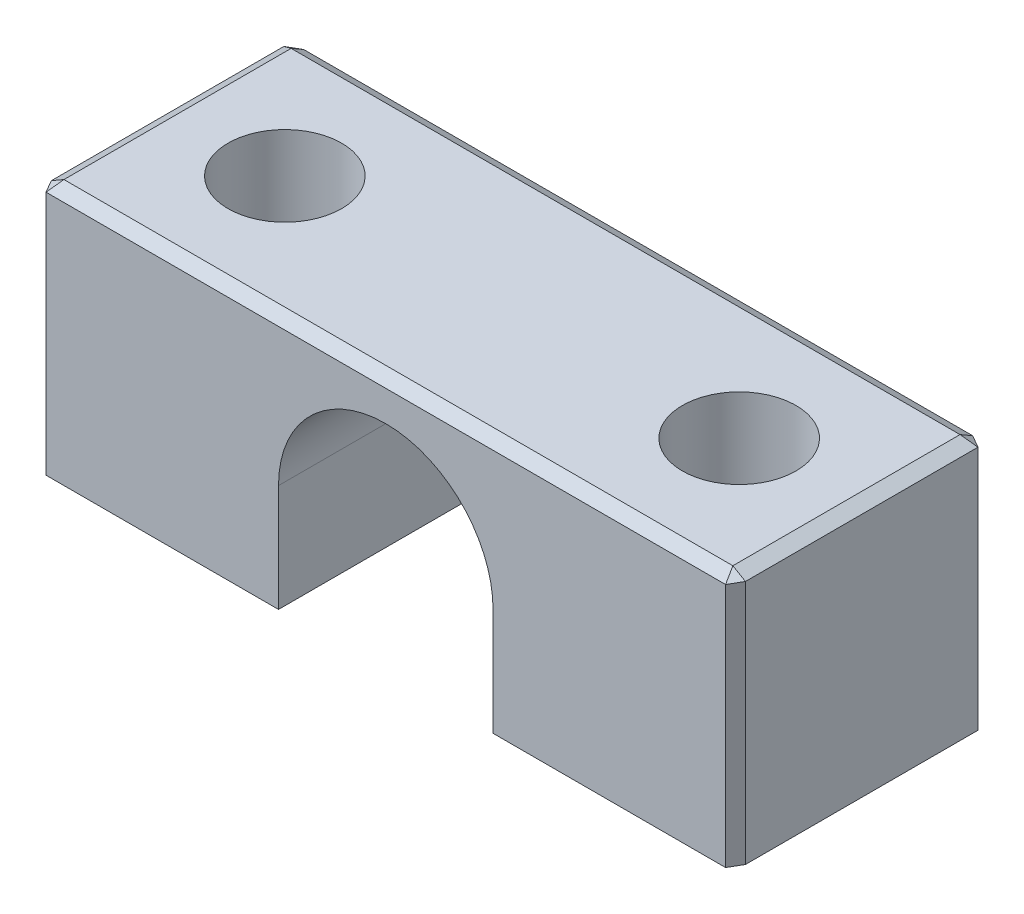
SolidWorks part; units mm, degrees
material "C40 or 38NiCrMo4"
ref_plane "Piano frontale" through (0, 0, 0) normal (0, 0, 1) x (1, 0, 0)
ref_plane "Piano superiore" through (0, 0, 0) normal (0, 1, 0) x (1, 0, 0)
ref_plane "Piano destro" through (0, 0, 0) normal (1, 0, 0) x (0, 0, -1)
sketch "Schizzo1" plane through (0, 0, 0) normal (0, 0, 1) x (1, 0, 0)
  line L0 (0, -905.0243) -> (0, 44346.1885) construction
  line L1 (-905.0243, 0) -> (44346.1885, 0) construction
  line L2 (-8.5, 8.5) -> (-8.5, 0)
  line L3 (-8.5, 0) -> (-27.5, 0)
  line L4 (-27.5, 0) -> (-27.5, 20)
  line L5 (-27.5, 20) -> (27.5, 20)
  line L6 (27.5, 0) -> (27.5, 20)
  line L7 (8.5, 0) -> (27.5, 0)
  line L8 (8.5, 8.5) -> (8.5, 0)
  arc A0 (8.5, 8.5) -> (-8.5, 8.5) centre (0, 8.5) ccw
  point P13 (0, 20)
  dimension "D1" = 17
  dimension "D2" = 8.5
  dimension "D3" = 19
  dimension "D4" = 20
extrude "Estrusione-Estrusione1" add sketch "Schizzo1" along normal blind 20
sketch "Schizzo2" plane through (0, 0, 0) normal (0, -1, 0) x (1, 0, 0)
  line L0 (-1027.5, 10) -> (48972.5, 10) construction
  line L1 (-27.5, 20) -> (-27.5, 0) construction
  line L2 (-18, -980) -> (-18, 49020) construction
  line L3 (-27.5, 20) -> (-8.5, 20) construction
  line L4 (18, -980) -> (18, 49020) construction
  line L5 (8.5, 20) -> (27.5, 20) construction
  circle A0 centre (-18, 10) radius 4.5
  circle A1 centre (18, 10) radius 4.5
  point P5 (-27.5, 10)
  point P10 (-18, 20)
  point P15 (18, 20)
  dimension "D1" = 9
  dimension "D2" = 9
extrude "Taglio-Estrusione1" cut sketch "Schizzo2" against normal through all
chamfer "Smusso1" distance 1 angle 30 8 edges at (27.5, 10, 0) (-27.5, 10, 0) (-27.5, 10, 20) (27.5, 10, 20) (27.5, 20, 10) (0, 20, 0) (-27.5, 20, 10) (0, 20, 20)
